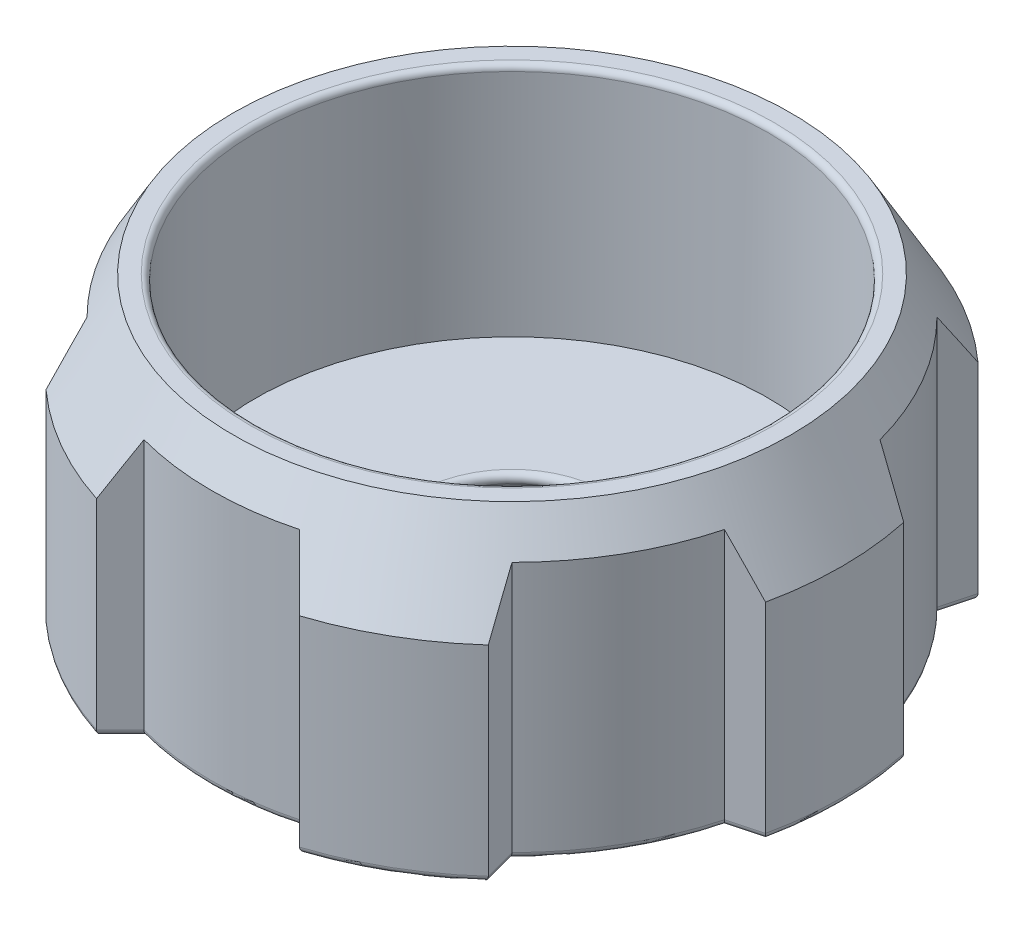
SolidWorks part; units mm, degrees
material "PET"
ref_plane "Front Plane" through (0, 0, 0) normal (0, 0, 1) x (1, 0, 0)
ref_plane "Top Plane" through (0, 0, 0) normal (0, 1, 0) x (1, 0, 0)
ref_plane "Right Plane" through (0, 0, 0) normal (1, 0, 0) x (0, 0, -1)
sketch "Sketch1" plane through (0, 0, 0) normal (0, 0, 1) x (1, 0, 0)
  line L0 (0, 0) -> (0, 12.4053) construction
  line L1 (20, 0) -> (14.2265, 10)
  line L2 (14.2265, 10) -> (43.5, 10)
  line L3 (43.5, 10) -> (43.5, 50)
  line L4 (43.5, 50) -> (47.3397, 50)
  line L5 (47.3397, 50) -> (56, 35)
  line L6 (56, 35) -> (56, 0)
  line L7 (56, 0) -> (20, 0)
  dimension "D1" = 40
  dimension "D2" = 60
  dimension "D3" = 87
  dimension "D4" = 112
  dimension "D5" = 10
  dimension "D6" = 30
  dimension "D7" = 40
  dimension "D8" = 15
revolve "body" add sketch "Sketch1" angle 360 about L0
sketch "Sketch5" plane through (0, 0, 0) normal (0, -1, 0) x (1, 0, 0)
  line L0 (49.2622, 13.1998) -> (54.7583, 11.7271)
  line L1 (36.0624, 36.0624) -> (37.5351, 41.5586)
  line L2 (0, 0) -> (56, 0) construction
  arc A0 (49.2622, 13.1998) -> (36.0624, 36.0624) centre (0, 0) ccw
  circle A1 centre (0, 0) radius 56 construction
  dimension "D3" = 5
  dimension "D1" = 30
  dimension "D2" = 90
  dimension "D4" = 15
extrude "side_cutout" cut sketch "Sketch5" against normal through all and the other way through all flip side to cut
pattern_circular "side_cutout_pattern" count 6 over 360 about axis through (0, 0, 0) along (0, -1, 0) of "side_cutout"
fillet "overall_fillets" radius 1 27 edges at (14.2265, 10, 0) (20, 0, 0) (43.5, 50, 0) (28, 0, -48.4974) (15.2115, 0, -51.2739) (0, 0, -51) (-15.2115, 0, -51.2739) (-28, 0, -48.4974) (-36.7988, 0, -38.8105) (-44.1673, 0, -25.5) (-52.0103, 0, -12.4634) (-56, 0, 0) (-52.0103, 0, 12.4634) (-44.1673, 0, 25.5) (-36.7988, 0, 38.8105) (-28, 0, 48.4974) (-15.2115, 0, 51.2739) (0, 0, 51) (15.2115, 0, 51.2739) (28, 0, 48.4974) (36.7988, 0, 38.8105) (44.1673, 0, 25.5) (52.0103, 0, 12.4634) (56, 0, 0) (52.0103, 0, -12.4634) (44.1673, 0, -25.5) (36.7988, 0, -38.8105)
sketch "screw_hole_pos" plane through (0, 0, 0) normal (0, -1, 0) x (1, 0, 0)
  point P0 (46, 0)
  dimension "D1" = 46
hole_wizard "screw_holes" positions "screw_hole_pos" profile "Sketch4" hole size "Ø2.7" standard "DIN"
sketch "Sketch4" plane through (46, 0, 0) normal (1, 0, 0) x (0, 0, -1)
  line L0 (0, 0) -> (0, 8.8112)
  line L1 (0, 8.8112) -> (1.35, 8)
  line L2 (1.35, 8) -> (1.35, 0.3)
  line L3 (1.35, 0.3) -> (1.65, 0)
  line L5 (1.65, 0) -> (0, 0)
  line L6 (-1.35, 0.3) -> (-1.65, 0) construction
  line L10 (0, 8.8112) -> (-1.35, 8) construction
  line L11 (0, -6.35) -> (0, 107.95) construction
  dimension "Hole Dia." = 2.7
  dimension "Hole Depth" = 8
  dimension "Near C'Sink Dia." = 3.3
  dimension "Near C'Sink Angle" = 90
  dimension "Drill Angle" = 118
pattern_circular "screw_hole_pattern" count 6 over 360 about axis through (0, 0, 0) along (0, 1, 0) of "screw_holes"
equation "\"paper_size\" = 600mm"
equation "\"cb_roll_d_outer\" = 86mm"
equation "\"cb_roll_d_inner\" = 76mm"
equation "\"attached_len\" = \"spring_l_max\" * 2 - \"spring_l_min\" + 18"
equation "\"helper_d\" = 92mm"
equation "\"outer_d\" = 112mm"
equation "\"spring_l_max\" = 25mm"
equation "\"spring_l_min\" = 10mm"
equation "\"cone_d_larger\" = 40mm"
equation "\"cone_angle\" = 60deg"
equation "\"D2@Sketch1\"=\"cone_angle\""
equation "\"D4@Sketch1\"=\"outer_d\""
equation "\"D3@Sketch1\"=\"cb_roll_d_outer\" + 1"
equation "\"D1@Sketch1\"=\"cone_d_larger\""
equation "\"bottom_screw_ring_d\" = 92mm"
equation "\"D1@screw_hole_pos\"=\"bottom_screw_ring_d\" / 2"
